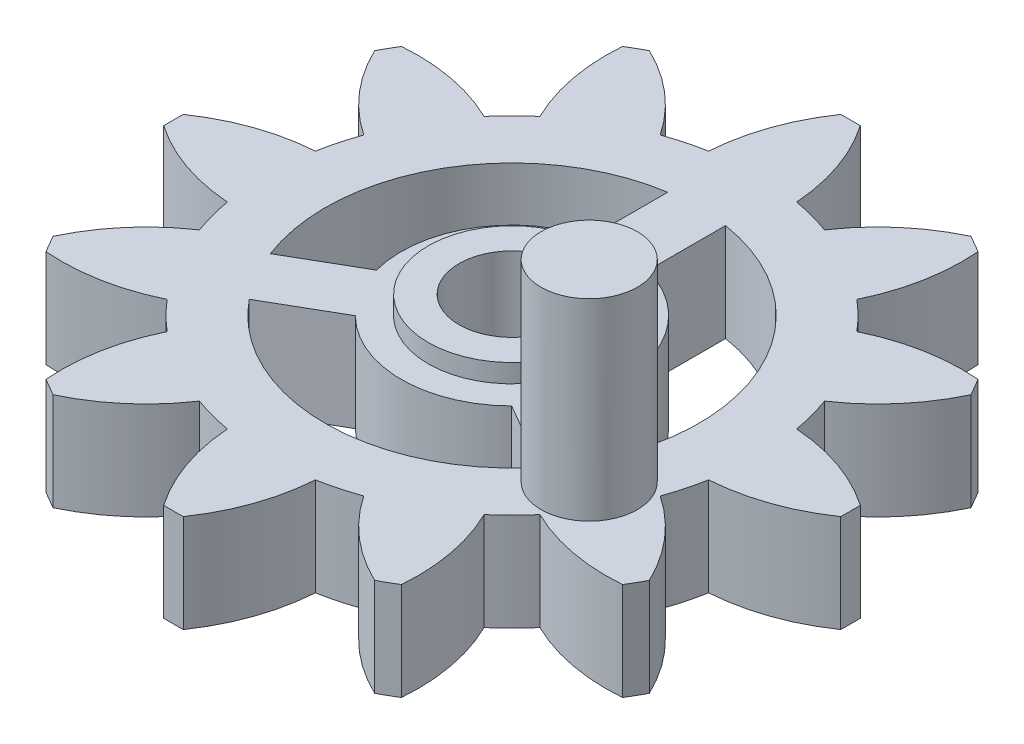
SolidWorks part; units mm, degrees
ref_plane "Front Plane" through (0, 0, 0) normal (0, 0, 1) x (1, 0, 0)
ref_plane "Top Plane" through (0, 0, 0) normal (0, 1, 0) x (1, 0, 0)
ref_plane "Right Plane" through (0, 0, 0) normal (1, 0, 0) x (0, 0, -1)
sketch "Base Profile" plane through (0, 0, 0) normal (0, 1, 0) x (1, 0, 0)
  circle A0 centre (0, 0) radius 12.7
  dimension "D1" = 25.4
extrude "Gear Base" add sketch "Base Profile" along normal mid plane 5.08
sketch "Tooth Profile" plane through (0, 0, 0) normal (0, 1, 0) x (1, 0, 0)
  line L0 (-0.508, 17.5726) -> (0.508, 17.5726) construction
  line L1 (0, 17.5726) -> (0, -12.9032) construction
  circle A0 centre (0, -12.9032) radius 30.48 construction
  arc A1 (-2.286, 12.4926) -> (-0.508, 17.5726) centre (7.8501, 11.7961) cw
  circle A2 centre (0, 0) radius 12.7 construction
  arc A3 (-0.508, 17.5726) -> (0.508, 17.5726) centre (0, -12.9032) cw
  arc A4 (2.286, 12.4926) -> (0.508, 17.5726) centre (-7.8501, 11.7961) ccw
  arc A5 (-2.286, 12.4926) -> (2.286, 12.4926) centre (0, 0) cw
  dimension "D1" = 60.96
  dimension "D2" = 10.16
  dimension "D3" = 1.016
  dimension "D4" = 5.08
  dimension "D5" = 4.572
extrude "Gear Tooth" add sketch "Tooth Profile" against normal up to surface (5.08 mm away) from surface at 2.54 up to face at (0, -2.54, 12.7) starting at face at (0, 2.54, 12.7)
pattern_circular "Pattern Tooth (12T)" count 12 over 360 about axis through (0, 0, 0) along (0, 1, 0) of "Gear Tooth"
sketch "Lip Profile" plane through (0, 0, 0) normal (0, 1, 0) x (1, 0, 0)
  circle A0 centre (0, 0) radius 4.3484
  dimension "D1" = 8.6967
extrude "Lip" add sketch "Lip Profile" along normal mid plane 7
sketch "Hole Profile" plane through (0, 2.54, 0) normal (0, 1, 0) x (1, 0, 0)
  circle A0 centre (0, 0) radius 2.75
  dimension "D1" = 5.5
extrude "Shaft Hole" cut sketch "Hole Profile" against normal up to surface (7 mm away) from surface at 0.96 up to face at (0, -3.5, 4.3484) starting at face at (0, 3.5, 4.3484)
sketch "Cutout Profile" plane through (0, 2.54, 0) normal (0, 1, 0) x (1, 0, 0)
  line L0 (-1.5, 9.5833) -> (-1.5, 5.5509)
  line L1 (1.5, 9.5833) -> (1.5, 5.5509)
  line L2 (-1.5, 9.5833) -> (1.5, 9.5833) construction
  line L3 (0, 9.5833) -> (0, 0) construction
  line L4 (9.0494, -3.4926) -> (5.5572, -1.4764)
  line L5 (7.5494, -6.0907) -> (4.0572, -4.0745)
  line L6 (-7.5494, -6.0907) -> (-4.0572, -4.0745)
  line L7 (-9.0494, -3.4926) -> (-5.5572, -1.4764)
  arc A0 (-7.5494, -6.0907) -> (7.5494, -6.0907) centre (0, 0) ccw
  arc A1 (-1.5, 5.5509) -> (-5.5572, -1.4764) centre (0, 0) ccw
  circle A2 centre (0, 0) radius 2.75 construction
  arc A3 (4.2665, 11.9619) -> (2.286, 12.4926) centre (0, 0) ccw construction
  arc A4 (9.0494, -3.4926) -> (1.5, 9.5833) centre (0, 0) ccw
  arc A5 (-1.5, 9.5833) -> (-9.0494, -3.4926) centre (0, 0) ccw
  arc A6 (-4.0572, -4.0745) -> (4.0572, -4.0745) centre (0, 0) ccw
  arc A7 (5.5572, -1.4764) -> (1.5, 5.5509) centre (0, 0) ccw
  dimension "D1" = 3
  dimension "D2" = 3
  dimension "D3" = 3
  dimension "D4" = 3
extrude "Gear Cutout" cut sketch "Cutout Profile" against normal up to surface (5.08 mm away)
sketch "Handle Profile" plane through (0, 2.54, 0) normal (0, 1, 0) x (1, 0, 0)
  line L2 (5.5572, -1.4764) -> (4.0572, -4.0745) construction
  line L3 (4.8072, -2.7755) -> (9.4838, -5.4755) construction
  circle A0 centre (9.4838, -5.4755) radius 2.5
  dimension "D2" = 5
  dimension "D1" = 5.4
extrude "Handle" add sketch "Handle Profile" along normal blind 10
